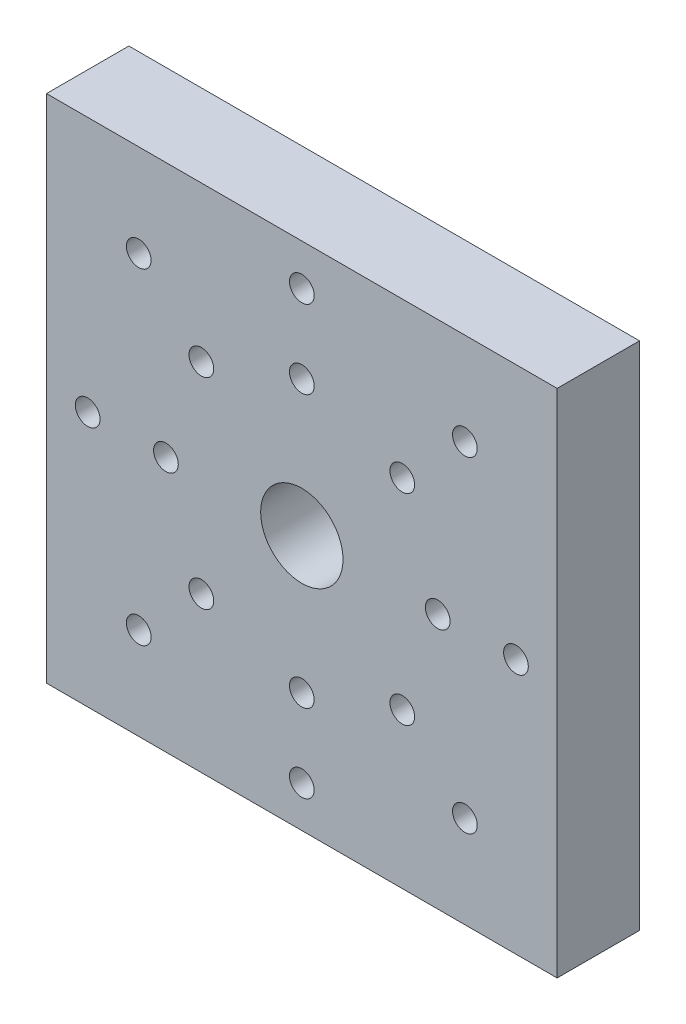
SolidWorks part; units mm, degrees
ref_plane "Front Plane" through (0, 0, 0) normal (0, 0, 1) x (1, 0, 0)
ref_plane "Top Plane" through (0, 0, 0) normal (0, 1, 0) x (1, 0, 0)
ref_plane "Right Plane" through (0, 0, 0) normal (1, 0, 0) x (0, 0, -1)
sketch "Sketch1" plane through (0, 0, 0) normal (0, 0, 1) x (1, 0, 0)
  line L0 (0, 0) -> (0, 16.5) construction
  line L1 (-31, 31) -> (31, 31)
  line L2 (-31, 31) -> (-31, -31)
  line L3 (-31, -31) -> (31, -31)
  line L4 (31, 31) -> (31, -31)
  line L5 (-31, 31) -> (31, -31) construction
  line L6 (-31, -31) -> (31, 31) construction
  line L7 (0, 0) -> (16.5, 0) construction
  line L8 (0, 0) -> (0, -16.5) construction
  line L9 (0, 0) -> (-16.5, 0) construction
  line L10 (0, 0) -> (0, 26.5081) construction
  circle A0 centre (0, 16.5) radius 1.5
  circle A1 centre (16.5, 0) radius 1.5
  circle A2 centre (0, -16.5) radius 1.5
  circle A3 centre (-16.5, 0) radius 1.5
  point P0 (0, 0)
  dimension "D7" = 3
  dimension "D8" = 3
  dimension "D9" = 3
  dimension "D10" = 3
  dimension "D1" = 62
  dimension "D2" = 62
  dimension "D3" = 16.5
  dimension "D4" = 16.5
  dimension "D5" = 16.5
  dimension "D6" = 16.5
extrude "Boss-Extrude1" add sketch "Sketch1" along normal blind 10
sketch "Sketch2" plane through (0, 0, 0) normal (0, 0, -1) x (-1, 0, 0)
  line L0 (0, 0) -> (-31, 31) construction
  line L1 (0, 0) -> (31, -31) construction
  line L2 (0, 0) -> (-31, -31) construction
  line L3 (31, -31) -> (-31, -31) construction
  line L4 (0, 0) -> (31, 31) construction
  line L5 (0, 0) -> (12.1976, 12.1976) construction
  line L6 (0, 0) -> (12.1976, -12.1976) construction
  line L7 (0, 0) -> (-12.1976, -12.1976) construction
  line L8 (0, 0) -> (-12.1976, 12.1976) construction
  circle A0 centre (-12.1976, 12.1976) radius 1.5
  circle A1 centre (-12.1976, -12.1976) radius 1.5
  circle A2 centre (12.1976, -12.1976) radius 1.5
  circle A3 centre (12.1976, 12.1976) radius 1.5
  dimension "D5" = 3
  dimension "D6" = 3
  dimension "D7" = 3
  dimension "D8" = 3
  dimension "D1" = 17.25
  dimension "D2" = 17.25
  dimension "D3" = 17.25
  dimension "D4" = 17.25
extrude "Cut-Extrude1" cut sketch "Sketch2" against normal blind 10
sketch "Sketch3" plane through (0, 0, 0) normal (0, 0, -1) x (-1, 0, 0)
  line L0 (0, 0) -> (0, 31) construction
  line L1 (-31, 31) -> (31, 31) construction
  line L2 (0, 0) -> (31, 0) construction
  line L3 (31, 31) -> (31, -31) construction
  line L4 (0, 0) -> (0, -31) construction
  line L5 (31, -31) -> (-31, -31) construction
  line L6 (0, 0) -> (-31, 0) construction
  line L7 (-31, -31) -> (-31, 31) construction
  line L8 (0, 0) -> (0, 26) construction
  line L9 (0, 0) -> (26, 0) construction
  line L10 (0, 0) -> (0, -26) construction
  line L11 (0, 0) -> (-26, 0) construction
  circle A0 centre (-26, 0) radius 1.5
  circle A1 centre (0, 26) radius 1.5
  circle A2 centre (26, 0) radius 1.5
  circle A3 centre (0, -26) radius 1.5
  dimension "D5" = 3
  dimension "D6" = 3
  dimension "D7" = 3
  dimension "D8" = 3
  dimension "D1" = 26
  dimension "D2" = 26
  dimension "D3" = 26
  dimension "D4" = 26
extrude "Cut-Extrude2" cut sketch "Sketch3" against normal up to surface (10 mm away) up to face at (10.6976, 12.1976, 10)
sketch "Sketch4" plane through (0, 0, 0) normal (0, 0, -1) x (-1, 0, 0)
  line L0 (0, 0) -> (19.799, 19.799) construction
  line L1 (0, 0) -> (19.799, -19.799) construction
  line L2 (0, 0) -> (-19.799, -19.799) construction
  line L3 (0, 0) -> (-19.799, 19.799) construction
  circle A0 centre (0, 0) radius 5
  circle A1 centre (-19.799, 19.799) radius 1.5
  circle A2 centre (19.799, 19.799) radius 1.5
  circle A3 centre (19.799, -19.799) radius 1.5
  circle A4 centre (-19.799, -19.799) radius 1.5
  dimension "D1" = 10
  dimension "D6" = 3
  dimension "D7" = 3
  dimension "D8" = 3
  dimension "D9" = 3
  dimension "D2" = 28
  dimension "D3" = 28
  dimension "D4" = 28
  dimension "D5" = 28
extrude "Cut-Extrude3" cut sketch "Sketch4" against normal up to surface (10 mm away) up to face at (27.5, 0, 10)
